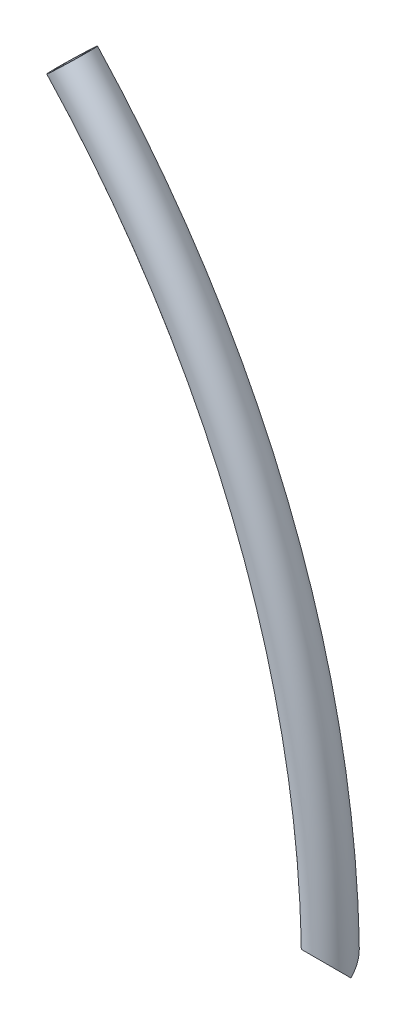
SolidWorks part; units mm, degrees
material "PVC Rigid"
ref_plane "Front Plane" through (0, 0, 0) normal (0, 0, 1) x (1, 0, 0)
ref_plane "Top Plane" through (0, 0, 0) normal (0, 1, 0) x (1, 0, 0)
ref_plane "Right Plane" through (0, 0, 0) normal (1, 0, 0) x (0, 0, -1)
sketch "Sketch1" plane through (0, 0, 0) normal (0, 0, 1) x (1, 0, 0)
  line L0 (0, 500) -> (0, 0) construction
  line L1 (0, 0) -> (500, 0) construction
  line L2 (0, 0) -> (353.5534, 353.5534) construction
  arc A0 (0, 500) -> (500, 0) centre (0, 0) cw
  dimension "D1" = 500
  dimension "D2" = 45
sketch "Sketch2" plane through (0, 0, 0) normal (0, 1, 0) x (1, 0, 0)
  line L0 (0, 0) -> (500, 0) construction
  circle A0 centre (500, 0) radius 7.8994
  circle A1 centre (500, 0) radius 10.668
  dimension "D1" = 15.7988
  dimension "D2" = 2.7686
sweep "Sweep1" add profiles "Sketch2" path "Sketch1"
sketch "Sketch3" plane through (0, 0, 0) normal (0, 1, 0) x (1, 0, 0)
  line L0 (0, 0) -> (10.668, 10.668)
  line L1 (500, 10.668) -> (0, 10.668) construction
  line L2 (10.668, 10.668) -> (-11.5753, 10.668)
  line L3 (-11.5753, 10.668) -> (-11.5753, -10.668)
  line L4 (-11.5753, -10.668) -> (10.668, -10.668)
  line L5 (0, -10.668) -> (500, -10.668) construction
  line L6 (10.668, -10.668) -> (0, 0)
  line L7 (0, -10.668) -> (500, -10.668) construction
  line L9 (10.668, -10.668) -> (10.668, 10.668) construction
  dimension "D1" = 90
sketch "Sketch4" plane through (0, 0, 0) normal (1, 0, 0) x (0, 0, -1)
  line L0 (0, 0) -> (-10.668, 10.668)
  line L1 (-10.668, 500) -> (-10.668, 0) construction
  line L2 (-10.668, 10.668) -> (-10.668, -2.0461)
  line L3 (-10.668, -2.0461) -> (10.668, -2.0461)
  line L4 (10.668, -2.0461) -> (10.668, 10.668)
  line L5 (10.668, 10.668) -> (0, 0)
  line L6 (-10.668, 10.668) -> (10.668, 10.668) construction
  line L8 (-10.668, 0) -> (0, 0) construction
  line L9 (-10.668, 0) -> (10.668, 0) construction
  line L10 (0, 0) -> (10.668, 0) construction
  dimension "D1" = 90
extrude "Cut-Extrude2" cut sketch "Sketch4" along normal through all
extrude "Cut-Extrude4" cut sketch "Sketch3" along normal up to next and the other way through all
ref_plane "Plane1" through (-97.9265, -91.318, -292.8917) normal (0.682, -0.7314, 0) x (-0.7314, -0.682, 0)
split "Split1" trim tools "Plane1" bodies to split 104 resulting bodies 105 106
delete or keep bodies "Body-Delete/Keep 1" type delete bodies bodies 106
sketch "Sketch5" plane through (0, 0, 0) normal (0, 0, 1) x (1, 0, 0)
  line L0 (357.8748, 333.7236) -> (373.4789, 348.2747) construction
  line L1 (489.332, 0) -> (510.668, 0) construction
  arc A0 (489.332, 0) -> (357.8748, 333.7236) centre (0, 0) ccw construction
  arc A1 (489.332, 0) -> (357.8748, 333.7236) centre (0, 0) ccw
  arc A2 (510.668, 0) -> (373.4789, 348.2747) centre (0, 0) ccw construction
  arc A3 (510.668, 0) -> (373.4789, 348.2747) centre (0, 0) ccw
  arc A4 (500, 0) -> (365.6769, 340.9992) centre (0, 0) ccw
  point P9 (500, 0)
  point P13 (365.6769, 340.9992)
  dimension "D1" = 489.332
